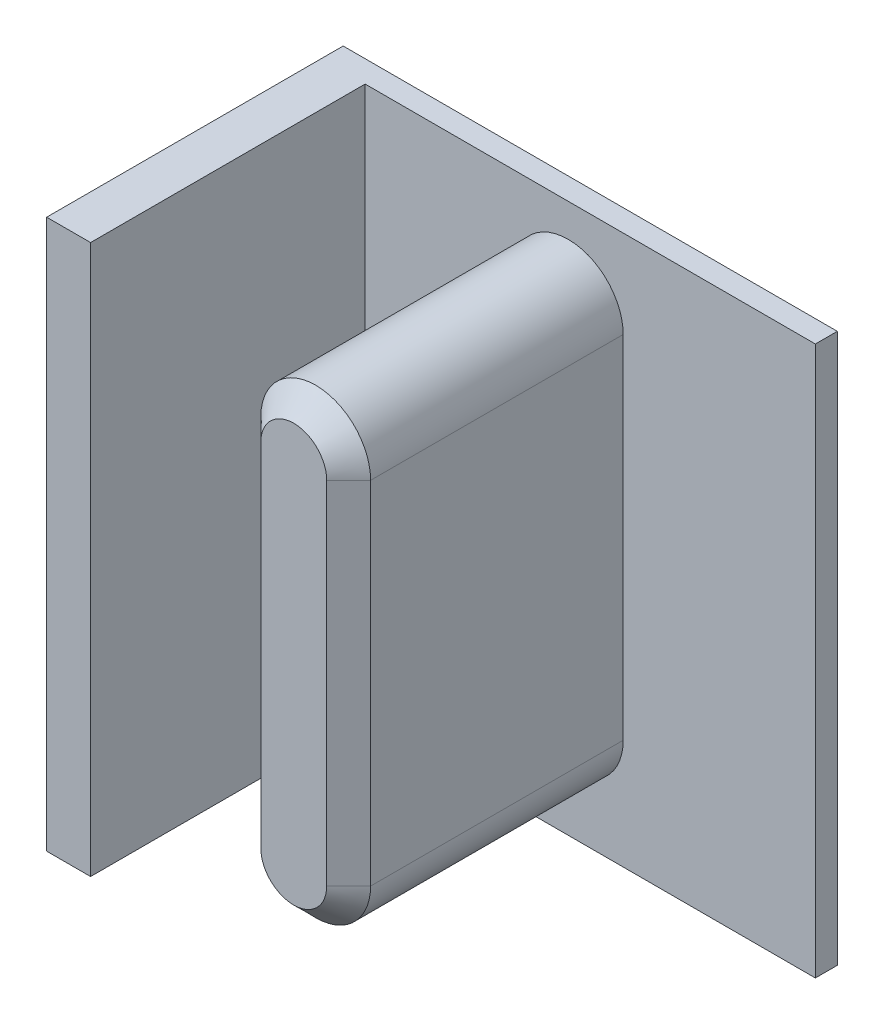
SolidWorks part; units mm, degrees
ref_plane "Front Plane" through (0, 0, 0) normal (0, 0, 1) x (1, 0, 0)
ref_plane "Top Plane" through (0, 0, 0) normal (0, 1, 0) x (1, 0, 0)
ref_plane "Right Plane" through (0, 0, 0) normal (1, 0, 0) x (0, 0, -1)
sketch "Sketch1" plane through (0, 0, 0) normal (0, 0, 1) x (1, 0, 0)
  line L1 (0, 0) -> (9, 0)
  line L2 (0, 0) -> (0, 10)
  line L3 (0, 10) -> (9, 10)
  line L4 (9, 0) -> (9, 10)
  dimension "D1" = 9
  dimension "D2" = 10
extrude "Boss-Extrude1" add sketch "Sketch1" along normal blind 0.4
sketch "Sketch3" plane through (0, 0, 0.4) normal (0, 0, 1) x (1, 0, 0)
  line L0 (4.5, 2) -> (4.5, 8.4) construction
  line L1 (3.5, 2) -> (3.5, 8.4)
  line L2 (5.5, 2) -> (5.5, 8.4)
  line L3 (9, 0) -> (9, 10) construction
  line L4 (0, 0) -> (9, 0) construction
  arc A0 (3.5, 2) -> (5.5, 2) centre (4.5, 2) ccw
  arc A1 (5.5, 8.4) -> (3.5, 8.4) centre (4.5, 8.4) ccw
  point P2 (4.5, 5.2)
  dimension "D2" = 1
  dimension "D1" = 4.5
  dimension "D3" = 6.4
  dimension "D4" = 2
extrude "Boss-Extrude2" add sketch "Sketch3" along normal blind 5
sketch "Sketch4" plane through (0, 0, 0.4) normal (0, 0, 1) x (1, 0, 0)
  line L0 (0, 0) -> (9, 0) construction
  line L1 (0, 10) -> (0.8, 10)
  line L2 (0, 10) -> (0, 0)
  line L3 (0, 0) -> (0.8, 0)
  line L4 (0.8, 10) -> (0.8, 0)
  dimension "D1" = 0.8
extrude "Boss-Extrude3" add sketch "Sketch4" along normal blind 5
chamfer "Chamfer1" distance 0.4 angle 45 4 edges at (3.5, 5.2, 5.4) (4.5, 9.4, 5.4) (5.5, 5.2, 5.4) (4.5, 1, 5.4)
